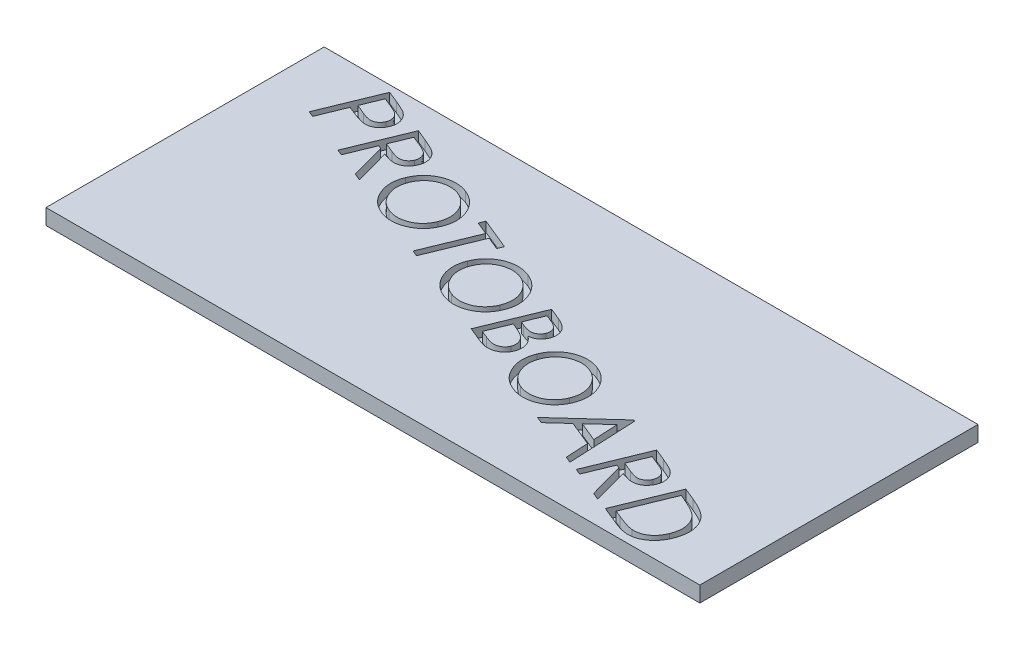
SolidWorks part; units mm, degrees
ref_plane "Front" through (0, 0, 0) normal (0, 0, 1) x (1, 0, 0)
ref_plane "Top" through (0, 0, 0) normal (0, 1, 0) x (1, 0, 0)
ref_plane "Right" through (0, 0, 0) normal (1, 0, 0) x (0, 0, -1)
sketch "Sketch1" plane through (0, 0, 0) normal (0, 1, 0) x (1, 0, 0)
  line L1 (-33.5, -14.25) -> (33.5, -14.25)
  line L2 (-33.5, -14.25) -> (-33.5, 14.25)
  line L3 (-33.5, 14.25) -> (33.5, 14.25)
  line L4 (33.5, -14.25) -> (33.5, 14.25)
  line L5 (-33.5, -14.25) -> (33.5, 14.25) construction
  line L6 (-33.5, 14.25) -> (33.5, -14.25) construction
  point P0 (0, 0)
  dimension "D1" = 28.5
  dimension "D2" = 67
extrude "Boss-Extrude1" add sketch "Sketch1" along normal mid plane 1.6
sketch "Sketch2" plane through (0, 0.8, 0) normal (0, 1, 0) x (1, 0, 0)
  line L0 (-29.2191, 8.0293) -> (25.5419, -13.7541) construction
  text T0 "PROTOBOARD"
extrude "Cut-Extrude1" cut sketch "Sketch2" against normal blind 1
